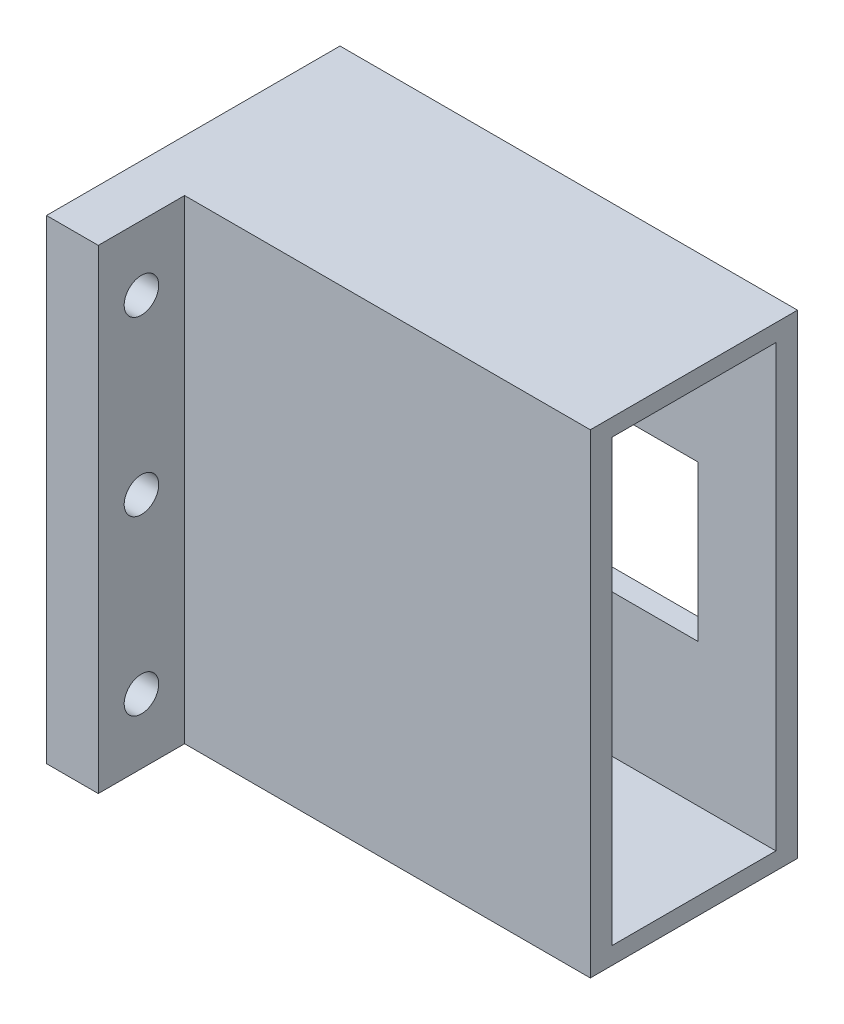
SolidWorks part; units mm, degrees
ref_plane "Front Plane" through (0, 0, 0) normal (0, 0, 1) x (1, 0, 0)
ref_plane "Top Plane" through (0, 0, 0) normal (0, 1, 0) x (1, 0, 0)
ref_plane "Right Plane" through (0, 0, 0) normal (1, 0, 0) x (0, 0, -1)
sketch "Sketch1" plane through (0, 0, 0) normal (0, 0, 1) x (1, 0, 0)
  line L1 (-13.25, -13.75) -> (13.25, -13.75)
  line L2 (-13.25, -13.75) -> (-13.25, 13.75)
  line L3 (-13.25, 13.75) -> (13.25, 13.75)
  line L4 (13.25, -13.75) -> (13.25, 13.75)
  line L5 (-13.25, -13.75) -> (13.25, 13.75) construction
  line L6 (-13.25, 13.75) -> (13.25, -13.75) construction
  point P0 (0, 0)
extrude "Boss-Extrude1" add sketch "Sketch1" along normal blind 12
sketch "Sketch3" plane through (13.25, 0, 0) normal (1, 0, 0) x (0, 0, -1)
  line L0 (0, 0) -> (-12, 0) construction
  line L1 (-12, -13.75) -> (-12, 13.75) construction
  line L3 (-10.75, -12.75) -> (-1.25, -12.75)
  line L4 (-10.75, -12.75) -> (-10.75, 12.75)
  line L5 (-10.75, 12.75) -> (-1.25, 12.75)
  line L6 (-1.25, -12.75) -> (-1.25, 12.75)
  line L7 (-10.75, -12.75) -> (-1.25, 12.75) construction
  line L8 (-10.75, 12.75) -> (-1.25, -12.75) construction
  point P5 (-6, 0)
extrude "Cut-Extrude1" cut sketch "Sketch3" against normal blind 24.5
sketch "Sketch4" plane through (0, 0, 0) normal (0, 0, -1) x (-1, 0, 0)
  line L0 (13.25, -13.75) -> (11.25, -13.75) construction
  line L1 (13.25, -13.75) -> (-13.25, -13.75) construction
  line L10 (0.25, -4.5) -> (-8.75, -4.5)
  line L11 (0.25, -4.5) -> (0.25, 4.5)
  line L12 (0.25, 4.5) -> (-8.75, 4.5)
  line L13 (-8.75, -4.5) -> (-8.75, 4.5)
extrude "Cut-Extrude2" cut sketch "Sketch4" against normal blind 3.5
sketch "Sketch6" plane through (0, 0, 12) normal (0, 0, 1) x (1, 0, 0)
  line L0 (-13.25, -13.75) -> (13.25, -13.75) construction
  line L1 (-13.25, 13.75) -> (-10.25, 13.75)
  line L2 (-13.25, 13.75) -> (-13.25, -13.75)
  line L3 (-13.25, -13.75) -> (-10.25, -13.75)
  line L4 (-10.25, 13.75) -> (-10.25, -13.75)
extrude "Boss-Extrude2" add sketch "Sketch6" along normal blind 5
sketch "Sketch7" plane through (-10.25, 0, 0) normal (1, 0, 0) x (0, 0, -1)
  circle A1 centre (-14.5, -10) radius 1
  circle A2 centre (-14.5, 0) radius 1
  circle A3 centre (-14.5, 10) radius 1
extrude "Cut-Extrude3" cut sketch "Sketch7" against normal blind 5
